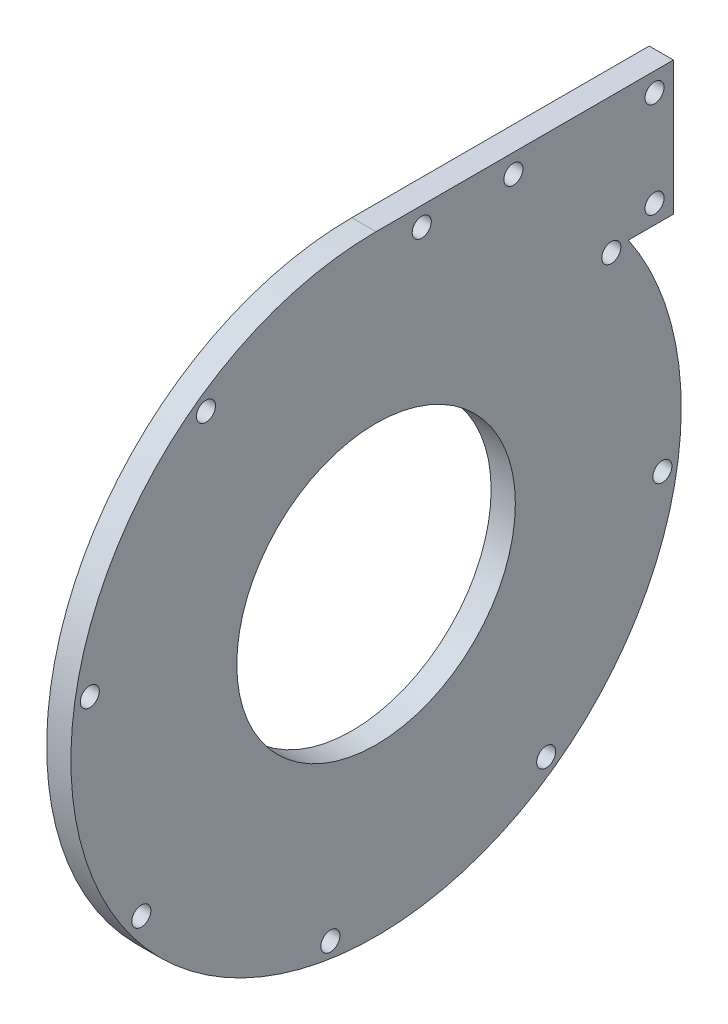
SolidWorks part; units mm, degrees
ref_plane "Front Plane" through (0, 0, 0) normal (0, 0, 1) x (1, 0, 0)
ref_plane "Top Plane" through (0, 0, 0) normal (0, 1, 0) x (1, 0, 0)
ref_plane "Right Plane" through (0, 0, 0) normal (1, 0, 0) x (0, 0, -1)
sketch "Sketch1" plane through (0, 0, 0) normal (1, 0, 0) x (0, 0, -1)
  line L1 (77.95, 0) -> (77.95, 77.95) construction
  line L4 (77.95, 80) -> (0, 80) construction
  line L5 (77.95, 45) -> (77.95, 80) construction
  line L6 (66.1438, 45) -> (77.95, 45) construction
  line L7 (77.95, 80) -> (0, 80)
  line L8 (77.95, 45) -> (77.95, 80)
  line L9 (66.1438, 45) -> (77.95, 45)
  circle A1 centre (0, 0) radius 36.5125
  arc A2 (0, 80) -> (66.1438, 45) centre (0, 0) ccw construction
  arc A3 (0, 80) -> (66.1438, 45) centre (0, 0) ccw
  dimension "D2" = 73.025
extrude "Boss-Extrude1" add sketch "Sketch1" along normal blind 6.35
sketch "Sketch3" plane through (6.35, 0, 0) normal (1, 0, 0) x (0, 0, -1)
  line L0 (77.95, 80) -> (0, 80) construction
  circle A0 centre (11.979, 75.05) radius 2.5
  dimension "D1" = 5
  dimension "D3" = 4.95
  dimension "D2" = 76
extrude "Cut-Extrude1" cut sketch "Sketch3" against normal through all
pattern_circular "CirPattern1" count 8 every 45 about axis through (0, 0, 0) along (1, 0, 0) skipping 7 of "Cut-Extrude1"
sketch "Sketch4" plane through (6.35, 0, 0) normal (1, 0, 0) x (0, 0, -1)
  line L3 (77.95, 80) -> (0, 80) construction
  line L4 (66.1438, 45) -> (77.95, 45) construction
  line L5 (77.95, 45) -> (77.95, 80) construction
  circle A0 centre (36, 75.05) radius 2.5
  circle A1 centre (73, 75.05) radius 2.5
  circle A2 centre (73, 49.95) radius 2.5
  circle A3 centre (61.6656, 44.4224) radius 2.5
  dimension "D1" = 37
  dimension "D2" = 4.95
  dimension "D3" = 4.95
  dimension "D4" = 4.95
  dimension "D5" = 76
extrude "Cut-Extrude4" cut sketch "Sketch4" against normal through all
